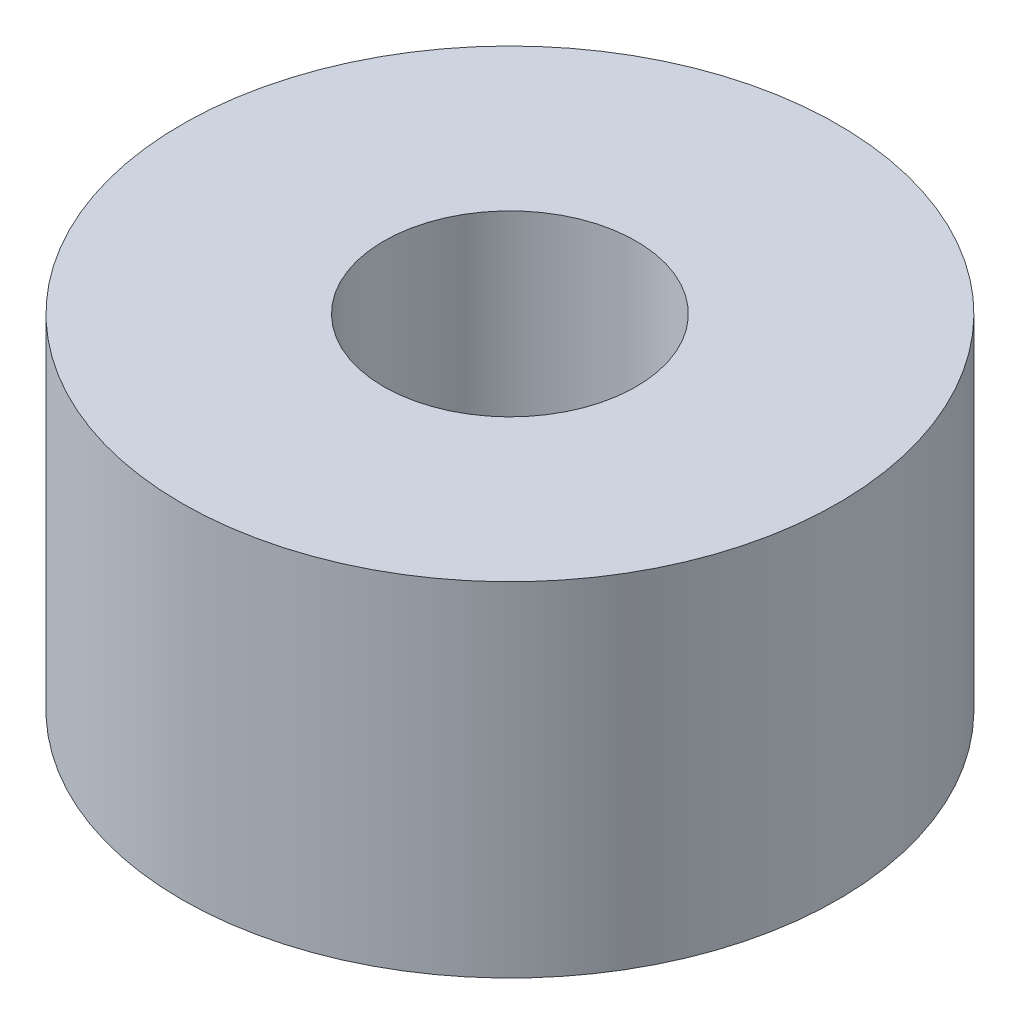
SolidWorks part; units mm, degrees
ref_plane "Front Plane" through (0, 0, 0) normal (0, 0, 1) x (1, 0, 0)
ref_plane "Top Plane" through (0, 0, 0) normal (0, 1, 0) x (1, 0, 0)
ref_plane "Right Plane" through (0, 0, 0) normal (1, 0, 0) x (0, 0, -1)
sketch "Sketch1" plane through (0, 0, 0) normal (0, 1, 0) x (1, 0, 0)
  circle A0 centre (0, 0) radius 1.25
  circle A1 centre (0, 0) radius 3.25
  dimension "D1" = 2.5
  dimension "D2" = 2
extrude "Body" add sketch "Sketch1" along normal blind 3.4
